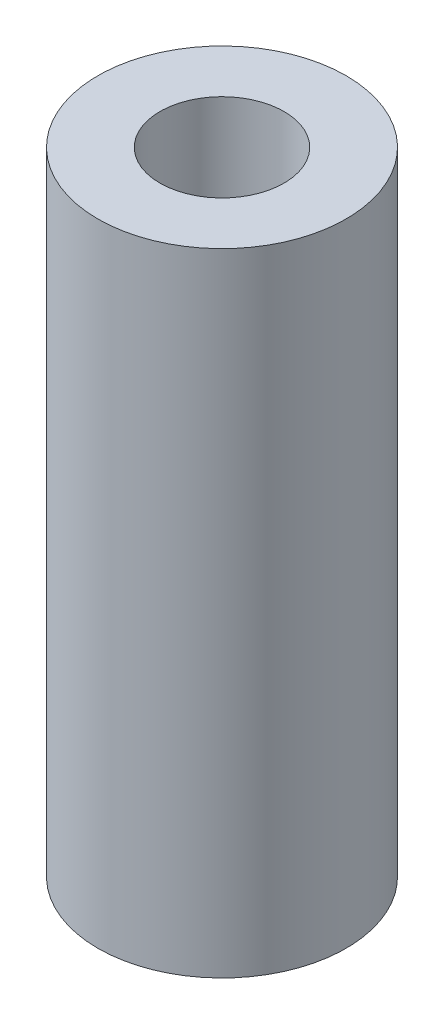
SolidWorks part; units mm, degrees
material "ABS"
ref_plane "前视基准面" through (0, 0, 0) normal (0, 0, 1) x (1, 0, 0)
ref_plane "上视基准面" through (0, 0, 0) normal (0, 1, 0) x (1, 0, 0)
ref_plane "右视基准面" through (0, 0, 0) normal (1, 0, 0) x (0, 0, -1)
other "Configuration Table"
sketch "草图1" plane through (0, 0, 0) normal (0, 1, 0) x (1, 0, 0)
  circle A0 centre (0, 0) radius 2.25
  circle A1 centre (0, 0) radius 4.5
  dimension "D1" = 4.5
  dimension "D2" = 9
extrude "凸台-拉伸1" add sketch "草图1" along normal blind 22.9
